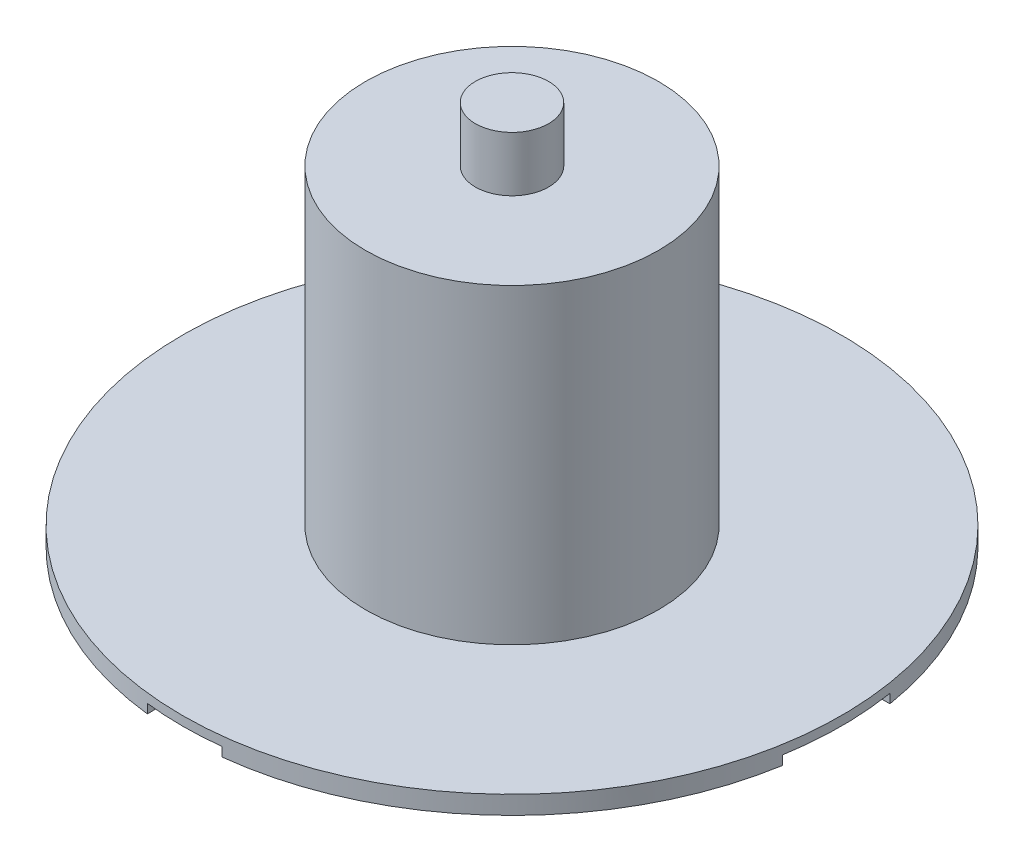
SolidWorks part; units mm, degrees
ref_plane "Спереди" through (0, 0, 0) normal (0, 0, 1) x (1, 0, 0)
ref_plane "Сверху" through (0, 0, 0) normal (0, 1, 0) x (1, 0, 0)
ref_plane "Справа" through (0, 0, 0) normal (1, 0, 0) x (0, 0, -1)
sketch "Эскиз1" plane through (0, 0, 0) normal (0, 1, 0) x (1, 0, 0)
  circle A0 centre (0, 0) radius 18
  dimension "D1" = 36
extrude "Бобышка-Вытянуть1" add sketch "Эскиз1" along normal blind 1
sketch "Эскиз2" plane through (0, 1, 0) normal (0, 1, 0) x (1, 0, 0)
  circle A0 centre (0, 0) radius 8
extrude "Бобышка-Вытянуть2" add sketch "Эскиз2" along normal blind 17
sketch "Эскиз3" plane through (0, 18, 0) normal (0, 1, 0) x (1, 0, 0)
  circle A0 centre (0, 0) radius 2
extrude "Бобышка-Вытянуть3" add sketch "Эскиз3" along normal blind 3
sketch "Эскиз4" plane through (0, 0, 0) normal (0, -1, 0) x (1, 0, 0)
  circle A0 centre (0, 0) radius 5
extrude "Вырез-Вытянуть1" cut sketch "Эскиз4" against normal blind 8
sketch "Эскиз5" plane through (0, 0, 0) normal (0, -1, 0) x (1, 0, 0)
  line L1 (-2.0352, 18) -> (2.0352, 18)
  line L2 (-2.0352, 18) -> (-2.0352, -18)
  line L3 (-2.0352, -18) -> (2.0352, -18)
  line L4 (2.0352, 18) -> (2.0352, -18)
  line L5 (-2.0352, 18) -> (2.0352, -18) construction
  line L6 (-2.0352, -18) -> (2.0352, 18) construction
  line L7 (-18, 2.983) -> (18, 2.983)
  line L8 (-18, 2.983) -> (-18, -2.8764)
  line L9 (-18, -2.8764) -> (18, -2.8764)
  line L10 (18, 2.983) -> (18, -2.8764)
  line L11 (-18, 2.983) -> (18, -2.8764) construction
  line L12 (-18, -2.8764) -> (18, 2.983) construction
  circle A0 centre (0, 0) radius 18 construction
  point P0 (0, 0)
  point P6 (0, 0.0533)
  circle M9 centre (0, 0) radius 5
  circle M10 centre (0, 0) radius 18
extrude "Вырез-Вытянуть2" cut sketch "Эскиз5" against normal blind 0.5 contours L9 L7 M10 M9 | L9 L2 L7 M9 | L9 L7 M9 M10 | L4 L9 L7 M9 | L4 L7 M9 | L2 L7 L4 M9 | L4 L2 M10 M9 | L2 L9 L4 L7 | L9 L4 M9 | L9 L2 L4 M9 | L9 L2 M9 | L7 L2 M9 | L4 L2 M9 M10
